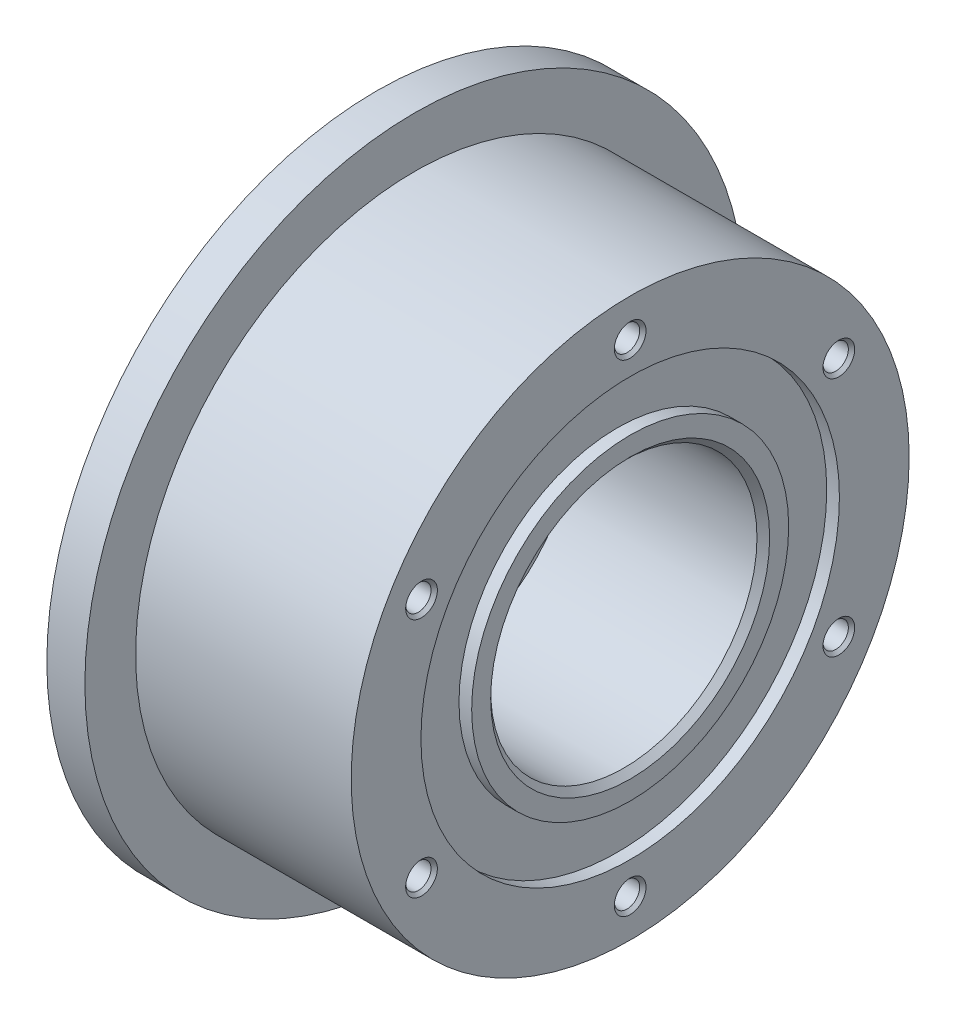
SolidWorks part; units mm, degrees
material "1023 Листовая углеродистая сталь (SS)"
ref_plane "Спереди" through (0, 0, 0) normal (0, 0, 1) x (1, 0, 0)
ref_plane "Сверху" through (0, 0, 0) normal (0, 1, 0) x (1, 0, 0)
ref_plane "Справа" through (0, 0, 0) normal (1, 0, 0) x (0, 0, -1)
sketch "Эскиз1" plane through (0, 0, 0) normal (0, 0, 1) x (1, 0, 0)
  line L0 (-2, 31) -> (-2, 0)
  line L1 (-2, 0) -> (35, 0)
  line L2 (35, 0) -> (35, 44)
  line L3 (35, 44) -> (1, 44)
  line L4 (1, 44) -> (1, 52)
  line L5 (1, 52) -> (-5, 52)
  line L6 (-5, 52) -> (-5, 38)
  line L7 (-5, 38) -> (15.5, 38)
  line L8 (15.5, 31) -> (-2, 31)
  line L9 (-5, 0) -> (35, 0) construction
  arc A0 (15.5, 38) -> (15.5, 31) centre (15.5, 34.5) cw
revolve "Повернуть1" add sketch "Эскиз1" angle 360 about L9
hole_wizard "Отверстие с зазором M561" positions "Эскиз3" profile "Эскиз2" hole size "M56" standard "Ansi Metric"
sketch "Эскиз3" plane through (35, 0, 0) normal (1, 0, 0) x (0, 0, -1)
  point P0 (0, 0)
sketch "Эскиз2" plane through (35, 0, 0) normal (0, 1, 0) x (0, 0, -1)
  line L0 (0, 0) -> (0, 2)
  line L1 (0, 2) -> (33, 2)
  line L2 (33, 2) -> (33, 0)
  line L5 (33, 0) -> (0, 0)
  line L10 (0, 2) -> (-33, 2) construction
  line L11 (0, -6.35) -> (0, 107.95) construction
  dimension "Диаметр отверстия" = 66
  dimension "Глубина отверстия" = 2
  dimension "Угол заточки сверла" = 180
sketch "Эскиз4" plane through (33, 0, 0) normal (1, 0, 0) x (0, 0, -1)
  circle A0 centre (0, 0) radius 25
extrude "Бобышка-Вытянуть1" add sketch "Эскиз4" along normal blind 2
sketch "Эскиз5" plane through (0, 0, 0) normal (0, 0, 1) x (1, 0, 0)
  line L0 (-2, 29) -> (-2, 0)
  line L1 (-2, 0) -> (35, 0)
  line L2 (35, 0) -> (35, 21)
  line L3 (35, 21) -> (5, 21)
  line L4 (5, 21) -> (5, 18)
  line L5 (5, 18) -> (0, 18)
  line L6 (0, 18) -> (0, 29)
  line L7 (0, 29) -> (-2, 29)
  line L8 (-2, 0) -> (35, 0) construction
revolve "Вырез-Повернуть1" cut sketch "Эскиз5" angle 360 about L8
hole_wizard "Диаметр отверстия Ø4.0 (4)1" positions "Эскиз7" profile "Эскиз6" hole size "Ø4.0" standard "Ansi Metric"
sketch "Эскиз7" plane through (35, 0, 0) normal (1, 0, 0) x (0, 0, -1)
  point P0 (-32.909, -19)
  point P1 (0, 38)
  point P2 (32.909, 19)
  point P3 (32.909, -19)
  point P4 (0, -38)
  point P5 (-32.909, 19)
sketch "Эскиз6" plane through (35, -19, 32.909) normal (0, 1, 0) x (0, 0, -1)
  line L0 (0, 0) -> (0, 10)
  line L1 (0, 10) -> (2, 10)
  line L2 (2, 10) -> (2, 0)
  line L5 (2, 0) -> (0, 0)
  line L10 (0, 10) -> (-2, 10) construction
  line L11 (0, -6.35) -> (0, 107.95) construction
  dimension "Диаметр отверстия" = 4
  dimension "Глубина отверстия" = 10
  dimension "Угол заточки сверла" = 180
hole_wizard "Диаметр отверстия Ø4.0 (4)2" positions "Эскиз9" profile "Эскиз8" hole size "Ø4.0" standard "Ansi Metric"
sketch "Эскиз9" plane through (0, 0, 0) normal (-1, 0, 0) x (0, 0, 1)
  point P0 (20.7846, 12)
  point P1 (-20.7846, 12)
  point P2 (0, -24)
  point P3 (20.7846, -12)
  point P4 (-20.7846, -12)
  point P5 (0, 24)
sketch "Эскиз8" plane through (0, 12, 20.7846) normal (0, 1, 0) x (0, 0, 1)
  line L0 (0, 0) -> (0, 10)
  line L1 (0, 10) -> (2, 10)
  line L2 (2, 10) -> (2, 0)
  line L5 (2, 0) -> (0, 0)
  line L10 (0, 10) -> (-2, 10) construction
  line L11 (0, -6.35) -> (0, 107.95) construction
  dimension "Диаметр отверстия" = 4
  dimension "Глубина отверстия" = 10
  dimension "Угол заточки сверла" = 180
chamfer "Фаска1" distance 1 angle 45 1 edges at (35, 0, -21)
chamfer "Фаска2" distance 0.5 angle 45 12 edges at (35, -19, 30.909) (35, -38, -2) (35, 19, -34.909) (0, 12, -18.7846) (0, 12, 22.7846) (0, -24, 2) (35, 38, -2) (0, -12, 22.7846) (35, -19, -34.909) (0, -12, -18.7846) (35, 19, 30.909) (0, 24, 2)
